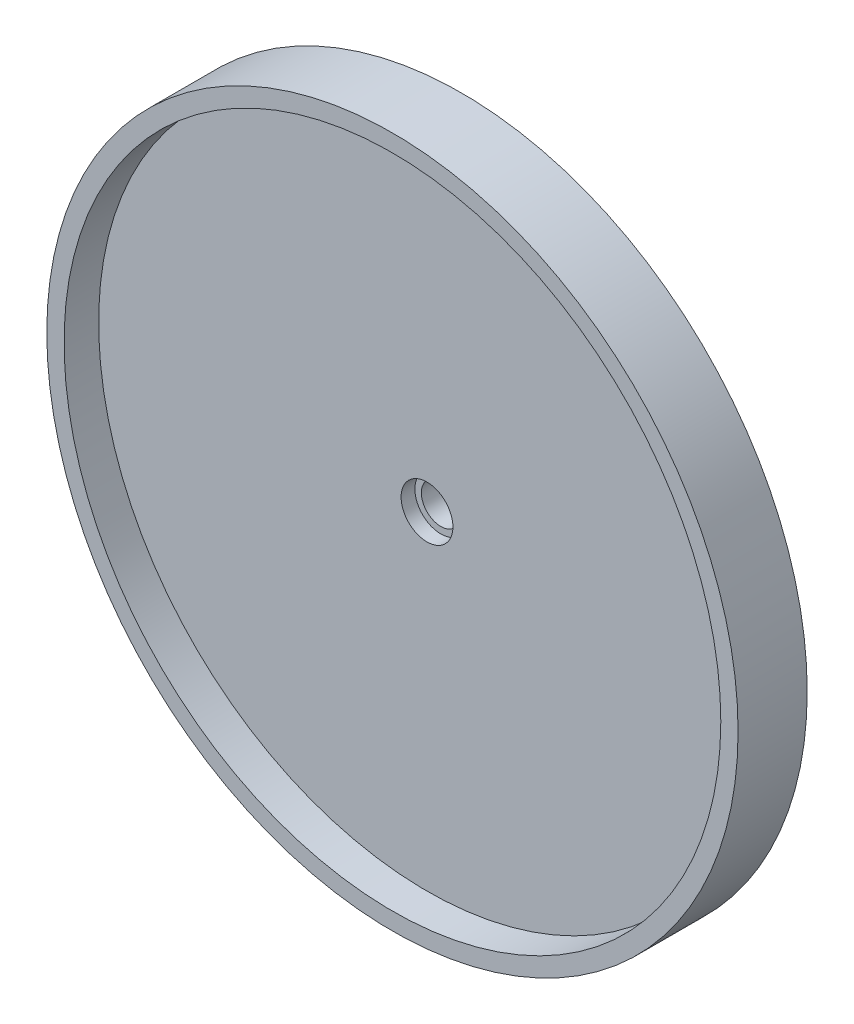
SolidWorks part; units mm, degrees
ref_plane "Front Plane" through (0, 0, 0) normal (0, 0, 1) x (1, 0, 0)
ref_plane "Top Plane" through (0, 0, 0) normal (0, 1, 0) x (1, 0, 0)
ref_plane "Right Plane" through (0, 0, 0) normal (1, 0, 0) x (0, 0, -1)
sketch "Sketch2" plane through (0, 0, 0) normal (1, 0, 0) x (0, 0, -1)
  line L0 (-40.5335, 0) -> (42.2066, 0) construction
  line L1 (0, 63.5) -> (0, 60.325)
  line L2 (0, 60.325) -> (6.35, 60.325)
  line L3 (6.35, 60.325) -> (6.35, 0)
  line L4 (6.35, 0) -> (12.7, 0)
  line L5 (12.7, 0) -> (12.7, 63.5)
  line L6 (12.7, 63.5) -> (0, 63.5)
  dimension "D1" = 12.7
  dimension "D2" = 127
  dimension "D3" = 120.65
  dimension "D4" = 6.35
revolve "Revolve1" add sketch "Sketch2" angle 360 about L0
sketch "Sketch3" plane through (0, 0, -12.7) normal (0, 0, -1) x (-1, 0, 0)
  circle A0 centre (0, 0) radius 3.5719
  dimension "D1" = 7.1437
extrude "Cut-Extrude1" cut sketch "Sketch3" against normal up to next and the other way through all
sketch "Sketch4" plane through (0, 0, -6.35) normal (0, 0, 1) x (1, 0, 0)
  circle A0 centre (0, 0) radius 4.7625
  dimension "D1" = 9.525
extrude "Cut-Extrude2" cut sketch "Sketch4" against normal blind 2.54
